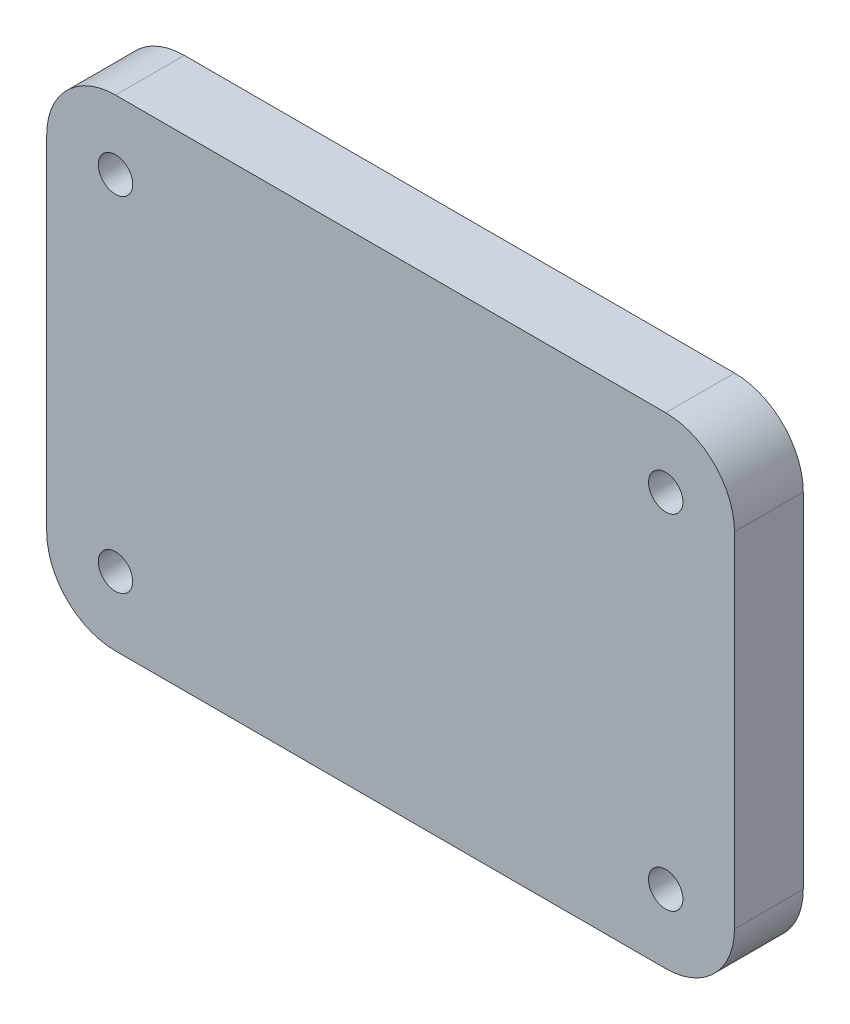
SolidWorks part; units mm, degrees
ref_plane "Front Plane" through (0, 0, 0) normal (0, 0, 1) x (1, 0, 0)
ref_plane "Top Plane" through (0, 0, 0) normal (0, 1, 0) x (1, 0, 0)
ref_plane "Right Plane" through (0, 0, 0) normal (1, 0, 0) x (0, 0, -1)
sketch "Sketch1" plane through (0, 0, 0) normal (0, 0, 1) x (1, 0, 0)
  line L0 (-50, 0) -> (50, 0) construction
  line L1 (-40, 35) -> (40, 35)
  line L2 (-50, 25) -> (-50, -25)
  line L3 (-40, -35) -> (40, -35)
  line L5 (50, 25) -> (50, -25)
  line L7 (0, -35) -> (0, 35) construction
  circle A0 centre (-40, 25) radius 2.5
  circle A1 centre (-40, -25) radius 2.5
  arc A2 (-40, 35) -> (-50, 25) centre (-40, 25) ccw
  arc A3 (-50, -25) -> (-40, -35) centre (-40, -25) ccw
  arc A4 (50, -25) -> (40, -35) centre (40, -25) cw
  arc A5 (40, 35) -> (50, 25) centre (40, 25) cw
  circle A6 centre (40, -25) radius 2.5
  circle A7 centre (40, 25) radius 2.5
  point P0 (0, 0)
  point P6 (-50, 25)
  point P7 (-50, -25)
  point P10 (0, 0)
  point P22 (0, 0)
  dimension "D3" = 5
  dimension "D4" = 5
  dimension "D1" = 50
  dimension "D2" = 70
  dimension "D5" = 10
  dimension "D6" = 25
extrude "Boss-Extrude1" add sketch "Sketch1" along normal blind 10
